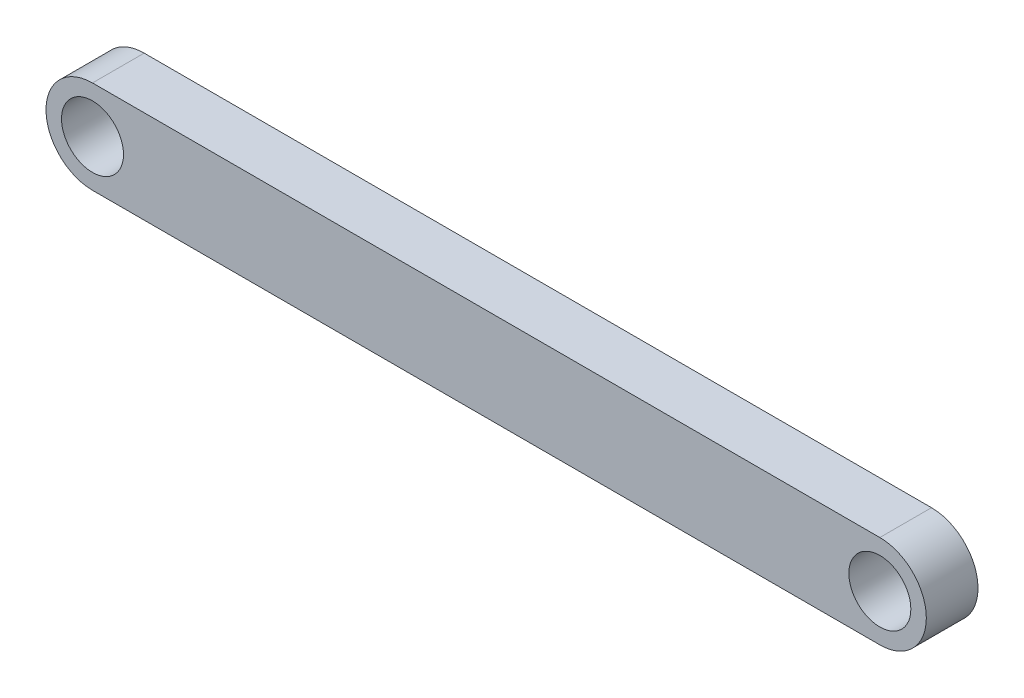
SolidWorks part; units mm, degrees
ref_plane "Front Plane" through (0, 0, 0) normal (0, 0, 1) x (1, 0, 0)
ref_plane "Top Plane" through (0, 0, 0) normal (0, 1, 0) x (1, 0, 0)
ref_plane "Right Plane" through (0, 0, 0) normal (1, 0, 0) x (0, 0, -1)
sketch "Sketch1" plane through (0, 0, 0) normal (0, 0, 1) x (1, 0, 0)
  line L0 (38.1, 0) -> (-38.1, 0) construction
  line L1 (38.1, -4.5) -> (-38.1, -4.5)
  line L2 (38.1, 4.5) -> (-38.1, 4.5)
  arc A0 (38.1, -4.5) -> (38.1, 4.5) centre (38.1, 0) ccw
  arc A1 (-38.1, 4.5) -> (-38.1, -4.5) centre (-38.1, 0) ccw
  point P2 (0, 0)
  dimension "D2" = 4.5
  dimension "D1" = 76.2
extrude "Boss-Extrude2" add sketch "Sketch1" along normal blind 5
sketch "Sketch2" plane through (0, 0, 5) normal (0, 0, 1) x (1, 0, 0)
  circle A0 centre (-38.1, 0) radius 3
  circle A1 centre (38.1, 0) radius 3
  dimension "D1" = 6
  dimension "D2" = 6
extrude "Cut-Extrude1" cut sketch "Sketch2" against normal through all
